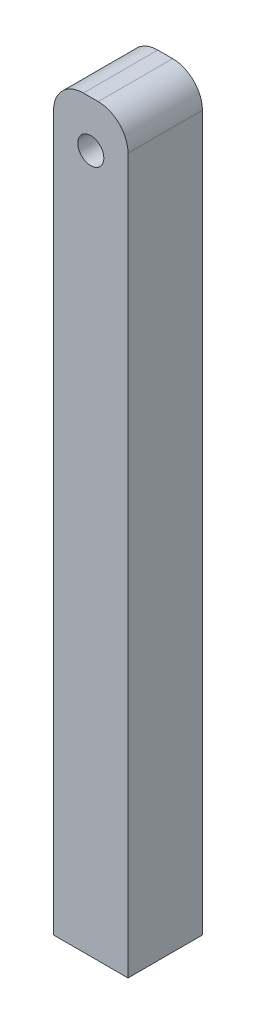
SolidWorks part; units mm, degrees
ref_plane "Alzado" through (0, 0, 0) normal (0, 0, 1) x (1, 0, 0)
ref_plane "Planta" through (0, 0, 0) normal (0, 1, 0) x (1, 0, 0)
ref_plane "Vista lateral" through (0, 0, 0) normal (1, 0, 0) x (0, 0, -1)
sketch "Croquis1" plane through (0, 0, 0) normal (0, 0, 1) x (1, 0, 0)
  line L1 (5, -50) -> (-5, -50)
  line L2 (5, -50) -> (5, 46)
  line L3 (1, 50) -> (-1, 50)
  line L4 (-5, -50) -> (-5, 46)
  line L5 (5, -50) -> (-5, 50) construction
  line L6 (5, 50) -> (-5, -50) construction
  arc A0 (5, 46) -> (1, 50) centre (1, 46) ccw
  arc A1 (-1, 50) -> (-5, 46) centre (-1, 46) ccw
  point P0 (0, 0)
  dimension "D3" = 4
  dimension "D1" = 100
  dimension "D2" = 10
extrude "Saliente-Extruir2" add sketch "Croquis1" along normal blind 10
sketch "Croquis2" plane through (0, 0, 10) normal (0, 0, 1) x (1, 0, 0)
  circle A0 centre (0, 43.7918) radius 1.75
  dimension "D1" = 3.5
extrude "Cortar-Extruir1" cut sketch "Croquis2" against normal blind 3
